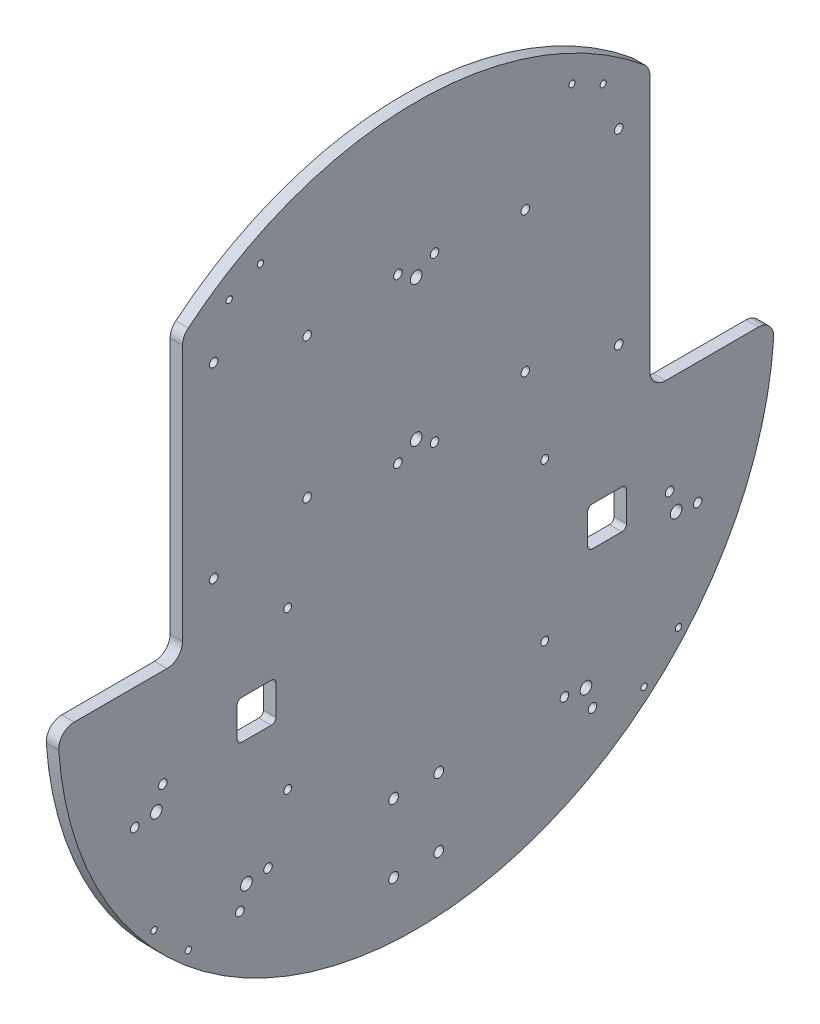
SolidWorks part; units mm, degrees
ref_plane "前视基准面" through (0, 0, 0) normal (0, 0, 1) x (1, 0, 0)
ref_plane "上视基准面" through (0, 0, 0) normal (0, 1, 0) x (1, 0, 0)
ref_plane "右视基准面" through (0, 0, 0) normal (1, 0, 0) x (0, 0, -1)
sketch "草图1" plane through (0, 0, 0) normal (1, 0, 0) x (0, 0, -1)
  circle A0 centre (0, 0) radius 230
  dimension "D1" = 460
extrude "凸台-拉伸1" add sketch "草图1" along normal blind 8
sketch "草图2" plane through (8, 0, 0) normal (1, 0, 0) x (0, 0, -1)
  line L0 (0, 0) -> (0, 50000) construction
  line L1 (-230, 195) -> (-230, -5)
  line L2 (150, 195) -> (230, 195)
  line L3 (150, 195) -> (150, -5)
  line L4 (150, -5) -> (230, -5)
  line L5 (230, 195) -> (230, -5)
  line L6 (-150, -5) -> (-230, -5)
  line L7 (-150, 195) -> (-150, -5)
  line L8 (-150, 195) -> (-230, 195)
  dimension "D1" = 200
  dimension "D2" = 80
  dimension "D3" = 150
  dimension "D4" = 5
extrude "切除-拉伸1" cut sketch "草图2" against normal blind 12
sketch "草图3" plane through (8, 0, 0) normal (1, 0, 0) x (0, 0, -1)
  line L0 (0, 0) -> (0, 50000) construction
  line L1 (-229.9456, -5) -> (-150, -5) construction
  line L2 (-130, 150) -> (-70, 150) construction
  line L3 (-130, 150) -> (-130, 30) construction
  line L4 (-130, 30) -> (-70, 30) construction
  line L5 (-70, 150) -> (-70, 30) construction
  line L6 (-150, -5) -> (-150, 174.356) construction
  line L7 (70, 150) -> (70, 30) construction
  line L8 (130, 30) -> (70, 30) construction
  line L9 (130, 150) -> (130, 30) construction
  line L10 (130, 150) -> (70, 150) construction
  circle A4 centre (-130, 150) radius 2.75
  circle A5 centre (-130, 30) radius 2.75
  circle A10 centre (130, 30) radius 2.75
  circle A11 centre (130, 150) radius 2.75
  circle A12 centre (-70, 135) radius 2.75
  circle A13 centre (-70, 45) radius 2.75
  circle A14 centre (70, 135) radius 2.75
  circle A15 centre (70, 45) radius 2.75
  dimension "D1" = 60
  dimension "D5" = 5.5
  dimension "D6" = 5.5
  dimension "D2" = 120
  dimension "D3" = 35
  dimension "D4" = 20
  dimension "D7" = 90
  dimension "D8" = 15
extrude "切除-拉伸2" cut sketch "草图3" against normal blind 12
sketch "草图4" plane through (8, 0, 0) normal (1, 0, 0) x (0, 0, -1)
  line L1 (-14.5, -150) -> (14.5, -150) construction
  line L2 (-14.5, -150) -> (-14.5, -194) construction
  line L3 (-14.5, -194) -> (14.5, -194) construction
  line L4 (14.5, -150) -> (14.5, -194) construction
  circle A0 centre (-14.5, -150) radius 3.15
  circle A1 centre (14.5, -150) radius 3.15
  circle A2 centre (14.5, -194) radius 3.15
  circle A3 centre (-14.5, -194) radius 3.15
  dimension "D5" = 6.3
  dimension "D1" = 44
  dimension "D2" = 29
  dimension "D3" = 14.5
  dimension "D4" = 150
extrude "切除-拉伸3" cut sketch "草图4" against normal blind 12
sketch "草图5" plane through (8, 0, 0) normal (1, 0, 0) x (0, 0, -1)
  line L0 (108.9626, -150.1738) -> (166.8134, -81.2298) construction
  line L1 (0, 0) -> (137.888, -115.7018) construction
  line L2 (0, 0) -> (0, 50000) construction
  line L3 (0, 0) -> (-137.888, -115.7018) construction
  line L4 (-108.9626, -150.1738) -> (-166.8134, -81.2298) construction
  line L5 (95.1406, -148.3663) -> (162.6333, -67.9317) construction
  circle A0 centre (166.8134, -81.2298) radius 3.75
  circle A1 centre (108.9626, -150.1738) radius 3.75
  circle A2 centre (-108.9626, -150.1738) radius 3.75
  circle A3 centre (-166.8134, -81.2298) radius 3.75
  circle A8 centre (-11.75, 35) radius 2.75
  circle A9 centre (11.75, 35) radius 2.75
  circle A10 centre (95.1406, -148.3663) radius 2.75
  circle A11 centre (162.6333, -67.9317) radius 2.75
  circle A12 centre (180.6354, -83.0372) radius 2.75
  circle A13 centre (113.1427, -163.4719) radius 2.75
  circle A14 centre (-180.6354, -83.0372) radius 2.75
  circle A15 centre (-162.6333, -67.9317) radius 2.75
  circle A16 centre (-95.1406, -148.3663) radius 2.75
  circle A17 centre (-113.1427, -163.4719) radius 2.75
  circle A22 centre (11.75, 140) radius 2.75
  circle A23 centre (-11.75, 140) radius 2.75
  circle A24 centre (0, 132.5) radius 3.75
  circle A25 centre (0, 42.5) radius 3.75
  dimension "D5" = 7.5
  dimension "D10" = 5.5
  dimension "D11" = 23.5
  dimension "D14" = 11.75
  dimension "D17" = 5.5
  dimension "D18" = 5.5
  dimension "D23" = 5.5
  dimension "D24" = 5.5
  dimension "D28" = 7.5
  dimension "D29" = 7.5
  dimension "D1" = 50
  dimension "D2" = 45
  dimension "D3" = 45
  dimension "D4" = 180
  dimension "D12" = 11.75
  dimension "D13" = 35
  dimension "D15" = 105
  dimension "D16" = 52.5
  dimension "D25" = 11.75
  dimension "D26" = 11.75
  dimension "D27" = 105
  dimension "D30" = 90
  dimension "D31" = 7.5
extrude "切除-拉伸4" cut sketch "草图5" against normal blind 10
fillet "圆角1" radius 10 6 edges at (4, 174.356, 150) (4, -5, 150) (4, -5, 229.9456) (4, 174.356, -150) (4, -5, -229.9456) (4, -5, -150)
sketch "草图6" plane through (8, 0, 0) normal (1, 0, 0) x (0, 0, -1)
  line L5 (-115, -45) -> (-90, -45)
  line L6 (-115, -45) -> (-115, -70)
  line L7 (-115, -70) -> (-90, -70)
  line L8 (-90, -45) -> (-90, -70)
  dimension "D1" = 25
  dimension "D2" = 25
  dimension "D3" = 90
  dimension "D4" = 45
extrude "切除-拉伸5" cut sketch "草图6" against normal blind 10
sketch "草图7" plane through (8, 0, 0) normal (1, 0, 0) x (0, 0, -1)
  line L1 (-82.5, -10) -> (82.5, -10) construction
  line L2 (-82.5, -10) -> (-82.5, -111) construction
  line L3 (-82.5, -111) -> (82.5, -111) construction
  line L4 (82.5, -10) -> (82.5, -111) construction
  circle A2 centre (82.5, -10) radius 2.5
  circle A3 centre (82.5, -111) radius 2.5
  circle A4 centre (-82.5, -10) radius 2.5
  circle A5 centre (-82.5, -111) radius 2.5
  dimension "D5" = 5
  dimension "D6" = 5
  dimension "D7" = 5
  dimension "D8" = 5
  dimension "D1" = 165
  dimension "D2" = 101
  dimension "D3" = 82.5
  dimension "D4" = 10
extrude "切除-拉伸6" cut sketch "草图7" against normal blind 10
sketch "草图8" plane through (8, 0, 0) normal (1, 0, 0) x (0, 0, -1)
  line L1 (110, -50) -> (135, -50)
  line L2 (110, -50) -> (110, -75)
  line L3 (110, -75) -> (135, -75)
  line L4 (135, -50) -> (135, -75)
  dimension "D1" = 25
  dimension "D2" = 25
  dimension "D3" = 50
  dimension "D4" = 110
extrude "切除-拉伸7" cut sketch "草图8" against normal blind 10
fillet "圆角3" radius 3 4 edges at (4, -75, -135) (4, -75, -110) (4, -50, -110) (4, -50, -135)
sketch "草图10" plane through (8, 0, 0) normal (1, 0, 0) x (0, 0, -1)
  line L0 (0, 0) -> (35355.3391, -35355.3391) construction
  line L1 (0, 0) -> (0, 50000) construction
  line L2 (146.3012, -168.3002) -> (0, 0) construction
  line L3 (0, 0) -> (168.3002, -146.3012) construction
  line L4 (0, 0) -> (-168.3002, -146.3012) construction
  line L5 (-146.3012, -168.3002) -> (0, 0) construction
  line L6 (0, 0) -> (-35355.3391, -35355.3391) construction
  circle A0 centre (168.3002, -146.3012) radius 2
  circle A1 centre (146.3012, -168.3002) radius 2
  circle A2 centre (-146.3012, -168.3002) radius 2
  circle A3 centre (-168.3002, -146.3012) radius 2
  dimension "D2" = 4
  dimension "D6" = 4
  dimension "D1" = 45
  dimension "D3" = 4
  dimension "D4" = 223
  dimension "D5" = 223
extrude "切除-拉伸9" cut sketch "草图10" against normal through all
sketch "草图11" plane through (8, 0, 0) normal (1, 0, 0) x (0, 0, -1)
  line L0 (0, 0) -> (0, 50000) construction
  circle A0 centre (100, 190) radius 2
  circle A1 centre (120, 180) radius 2
  circle A2 centre (-120, 180) radius 2
  circle A3 centre (-100, 190) radius 2
  dimension "D1" = 190
  dimension "D3" = 4
  dimension "D4" = 10
  dimension "D6" = 4
  dimension "D2" = 100
  dimension "D5" = 20
extrude "切除-拉伸10" cut sketch "草图11" against normal blind 25
fillet "圆角4" radius 3 4 edges at (4, -70, 90) (4, -70, 115) (4, -45, 115) (4, -45, 90)
